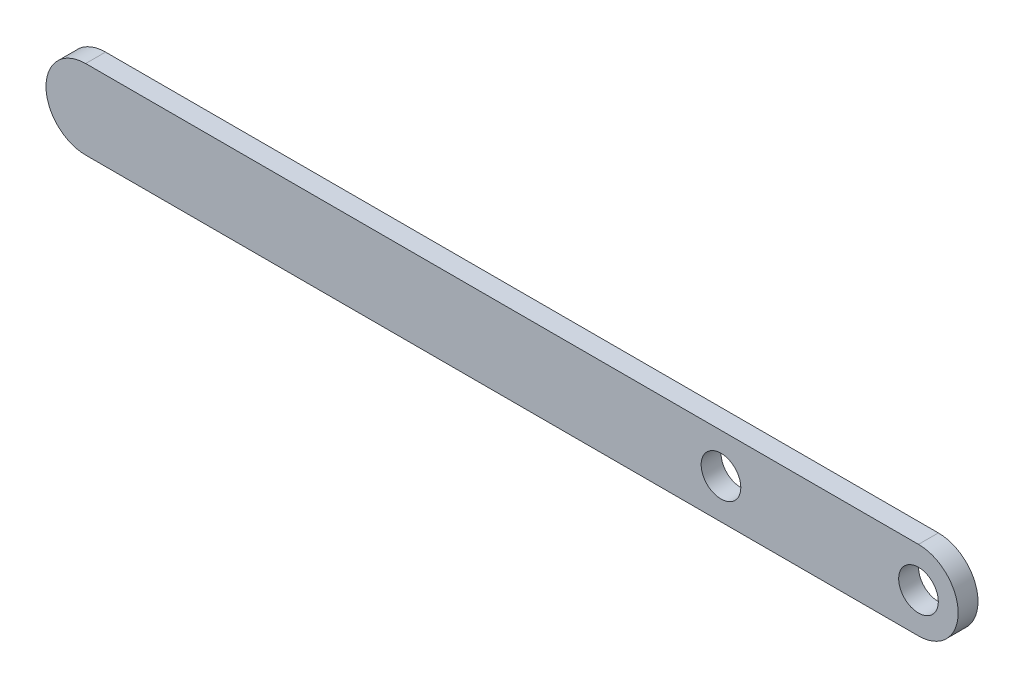
SolidWorks part; units mm, degrees
ref_plane "Front Plane" through (0, 0, 0) normal (0, 0, 1) x (1, 0, 0)
ref_plane "Top Plane" through (0, 0, 0) normal (0, 1, 0) x (1, 0, 0)
ref_plane "Right Plane" through (0, 0, 0) normal (1, 0, 0) x (0, 0, -1)
sketch "Sketch1" plane through (0, 0, 0) normal (0, 0, 1) x (1, 0, 0)
  line L0 (-54.3874, 0) -> (50.4828, 0) construction
  line L1 (-54.3874, 4.9938) -> (50.4828, 4.9938)
  line L2 (-54.3874, -4.9938) -> (50.4828, -4.9938)
  arc A0 (-54.3874, 4.9938) -> (-54.3874, -4.9938) centre (-54.3874, 0) ccw
  arc A1 (50.4828, -4.9938) -> (50.4828, 4.9938) centre (50.4828, 0) ccw
  circle A3 centre (50.4828, 0) radius 2.4969
  circle A4 centre (25.6126, 0) radius 2.4969
  point P3 (-1.9523, 0)
  dimension "D1" = 80
extrude "Boss-Extrude1" add sketch "Sketch1" along normal blind 2.5
sketch "Sketch2" plane through (0, 0, 2.5) normal (0, 0, 1) x (1, 0, 0)
  line L0 (-54.3874, 5) -> (-54.3874, -4.9938) construction
  circle A0 centre (-54.3874, 0) radius 5
  arc A1 (-54.3874, 4.9938) -> (-54.3874, -4.9938) centre (-54.3874, 0) ccw construction
